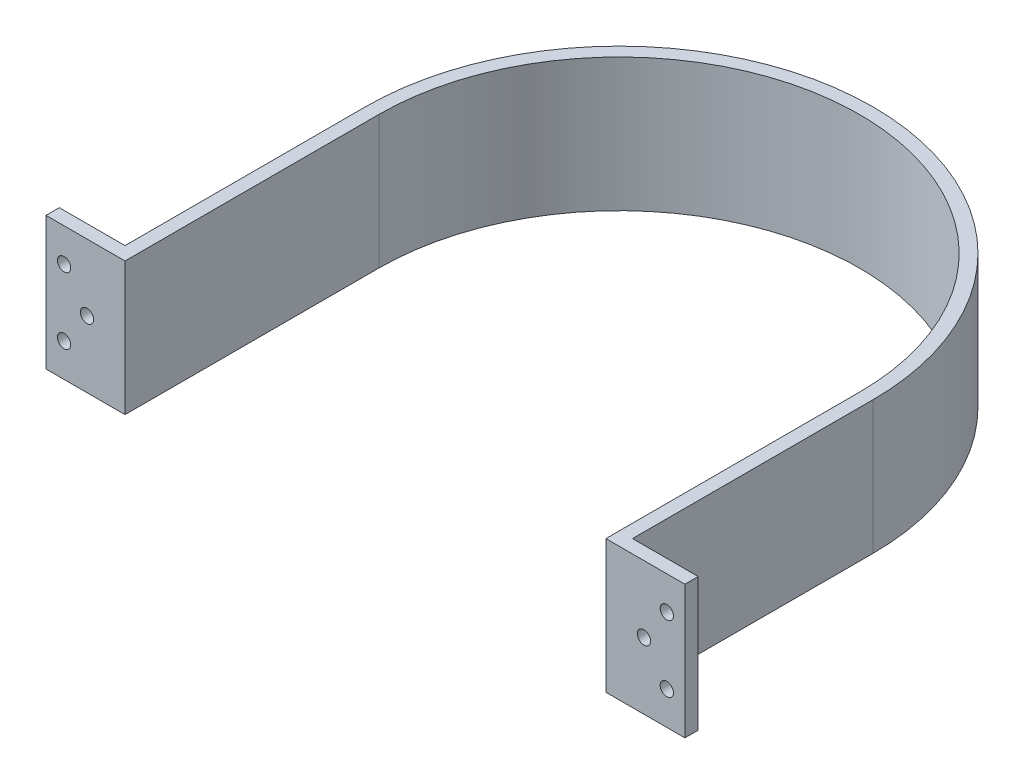
SolidWorks part; units mm, degrees
other "Markup1"
sketch "Sketch14" plane through (-178.835, 31.75, 121.05) normal (-0.0444, 0.3923, 0.9187) x (0.9976, 0.0664, 0.0198)
ref_plane "Front Plane" through (0, 0, 0) normal (0, 0, 1) x (1, 0, 0)
ref_plane "Top Plane" through (0, 0, 0) normal (0, 1, 0) x (1, 0, 0)
ref_plane "Right Plane" through (0, 0, 0) normal (1, 0, 0) x (0, 0, -1)
sketch "Sketch1" plane through (0, 0, 0) normal (0, 1, 0) x (1, 0, 0)
  line L0 (0, 0) -> (-121.05, 0) construction
  line L1 (0, 0) -> (0, -121.05) construction
  line L2 (0, -121.05) -> (-152.4, -121.05)
  line L3 (-114.7, 0) -> (-114.7, -121.05)
  line L4 (-121.05, 0) -> (-121.05, -121.05)
  line L5 (0, -114.7) -> (-152.4, -114.7)
  line L6 (-152.4, -114.7) -> (-152.4, -121.05)
  line L7 (-120.3819, -12.7) -> (-121.05, -12.7)
  line L8 (152.4, -114.7) -> (152.4, -121.05)
  line L9 (0, -114.7) -> (152.4, -114.7)
  line L10 (-113.9947, -12.7) -> (-114.7, -12.7)
  line L11 (121.05, 0) -> (121.05, -121.05)
  line L12 (114.7, 0) -> (114.7, -121.05)
  line L13 (0, -121.05) -> (152.4, -121.05)
  circle A0 centre (0, 0) radius 102
  circle A1 centre (0, 0) radius 114.7
  arc A3 (-114.7, -38.6912) -> (-121.05, 0) centre (0, 0) ccw
  arc A4 (-114.7, -38.6912) -> (119.5416, -19.05) centre (0, 0) ccw
  arc A5 (120.3819, -12.7) -> (120.3819, 12.7) centre (0, 0) ccw
  circle A6 centre (0, 0) radius 121.05 construction
  point P8 (-152.4, -117.875)
  point P29 (0, 0)
  dimension "D1" = 204
  dimension "D2" = 12.7
  dimension "D4" = 152.4
  dimension "D3" = 6.35
  dimension "D5" = 6.35
extrude "Boss-Extrude1" add sketch "Sketch1" along normal mid plane 63.5
sketch "Sketch15" plane through (0, 0, 121.05) normal (0, 0, 1) x (1, 0, 0)
  line L0 (-138.3125, 0) -> (-127.4, 0) construction
  line L5 (-127.4, 31.75) -> (-127.4, -31.75)
  line L6 (-127.4, 31.75) -> (-127.4, -31.75)
  line L7 (-138.3125, 0) -> (-138.3125, 31.75) construction
  line L8 (-149.225, 31.75) -> (-149.225, -31.75)
  line L9 (-149.225, 31.75) -> (-149.225, -31.75)
  line L10 (-114.7, 31.75) -> (-152.4, 31.75) construction
  line L11 (-138.3125, 15.875) -> (-149.225, 15.875) construction
  line L12 (0, 0) -> (0, 31.75) construction
  line L13 (114.7, 31.75) -> (-114.7, 31.75) construction
  circle A0 centre (-143.7688, 15.875) radius 3.175
  circle A1 centre (-143.7688, -15.875) radius 3.175
  circle A2 centre (-132.8563, 0) radius 3.175
  circle A3 centre (132.8563, 0) radius 3.175
  circle A4 centre (143.7688, -15.875) radius 3.175
  circle A5 centre (143.7688, 15.875) radius 3.175
  dimension "D1" = 12.7
  dimension "D2" = 3.175
extrude "Cut-Extrude1" cut sketch "Sketch15" against normal through all contours A0 | A2 | A1 | A3 | A5 | A4
